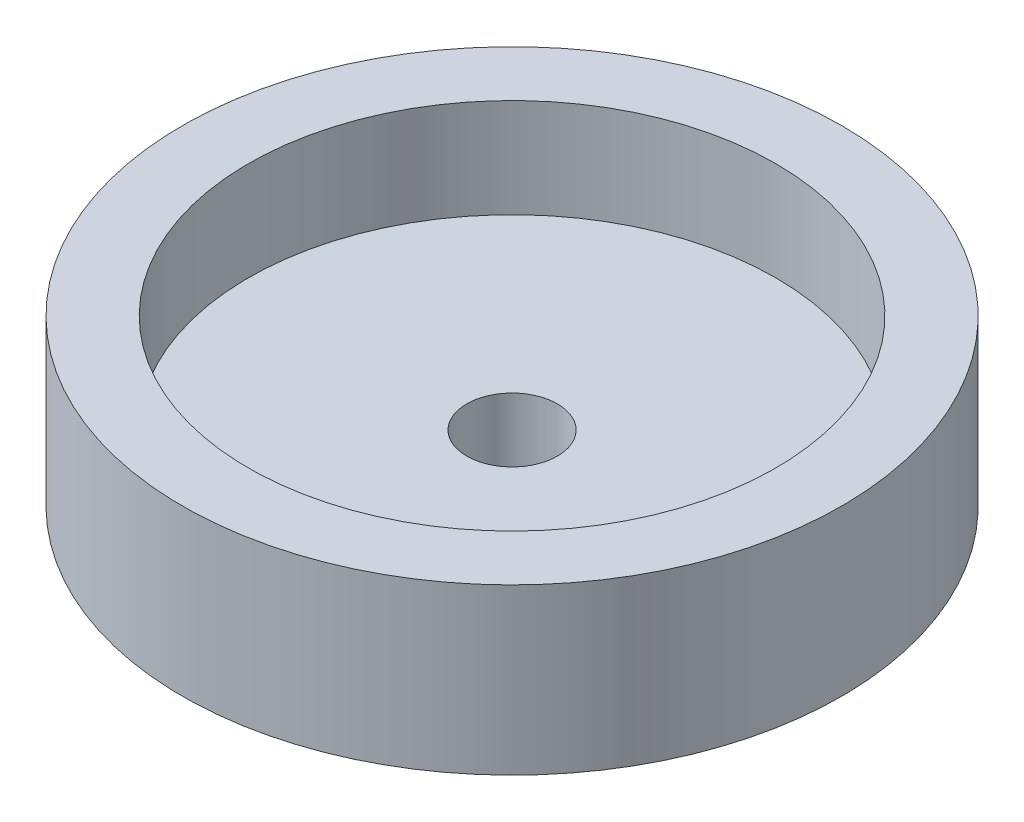
SolidWorks part; units mm, degrees
ref_plane "Front Plane" through (0, 0, 0) normal (0, 0, 1) x (1, 0, 0)
ref_plane "Top Plane" through (0, 0, 0) normal (0, 1, 0) x (1, 0, 0)
ref_plane "Right Plane" through (0, 0, 0) normal (1, 0, 0) x (0, 0, -1)
sketch "Sketch1" plane through (0, 0, 0) normal (0, 0, 1) x (1, 0, 0)
  line L1 (0, 0) -> (-16, 0)
  line L2 (0, 0) -> (0, 4)
  line L3 (0, 4) -> (-16, 4)
  line L4 (-16, 0) -> (-16, 4)
  line L5 (-20, 10) -> (-16, 10)
  line L6 (-20, 10) -> (-20, 0)
  line L7 (-20, 0) -> (-16, 0)
  line L8 (-16, 10) -> (-16, 0)
  dimension "D1" = 4
  dimension "D2" = 4
  dimension "D3" = 20
  dimension "D4" = 10
revolve "Revolve1" add sketch "Sketch1" angle 360 about L2
hole_wizard "M5 Clearance Hole1" positions "Sketch2" profile "Sketch3" hole size "M5" standard "ANSI Metric" end condition through all
sketch "Sketch2" plane through (0, 4, 0) normal (0, 1, 0) x (1, 0, 0)
  point P0 (0, 0)
sketch "Sketch3" plane through (0, 4, 0) normal (1, 0, 0) x (0, 0, 1)
  line L0 (0, 0) -> (0, 4)
  line L1 (0, 4) -> (2.75, 4)
  line L2 (2.75, 4) -> (2.75, 0)
  line L5 (2.75, 0) -> (0, 0)
  line L11 (0, -6.35) -> (0, 107.95) construction
  dimension "Thru Hole Dia." = 5.5
  dimension "Thru Hole Depth" = 4
